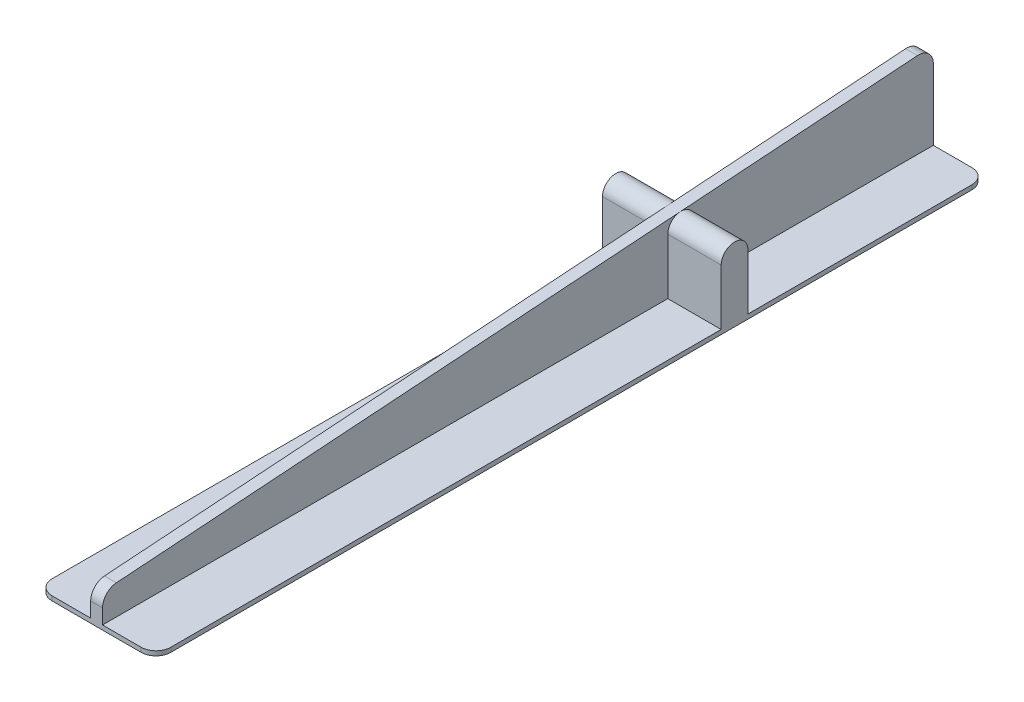
SolidWorks part; units mm, degrees
material "ABS"
ref_plane "Plan de face" through (0, 0, 0) normal (0, 0, 1) x (1, 0, 0)
ref_plane "Plan de dessus" through (0, 0, 0) normal (0, 1, 0) x (1, 0, 0)
ref_plane "Plan de droite" through (0, 0, 0) normal (1, 0, 0) x (0, 0, -1)
sketch "Esquisse1" plane through (0, 0, 0) normal (0, 0, 1) x (1, 0, 0)
  line L0 (2, 1.5) -> (20, 1.5)
  line L1 (-2, 41.5) -> (2, 41.5)
  line L2 (-2, 41.5) -> (-2, 1.5)
  line L4 (2, 41.5) -> (2, 1.5)
  line L5 (-20, 0) -> (20, 0)
  line L6 (-20, 0) -> (-20, 1.5)
  line L7 (-20, 1.5) -> (-2, 1.5)
  line L8 (20, 0) -> (20, 1.5)
  dimension "D1" = 1.5
  dimension "D2" = 40
  dimension "D3" = 4
  dimension "D4" = 40
  dimension "D5" = 18
extrude "Boss.-Extru.1" add sketch "Esquisse1" along normal blind 280 from offset 85 offset against normal yes
sketch "Esquisse3" plane through (2, 0, 0) normal (1, 0, 0) x (0, 0, -1)
  line L0 (85, 1.5) -> (85, 41.5) construction
  line L1 (-195, 41.5) -> (85, 41.5)
  line L2 (-195, 41.5) -> (-195, 11.1643)
  line L3 (-195, 11.1643) -> (85, 30.7438)
  line L4 (85, 41.5) -> (85, 30.7438)
  line L5 (0, 24.8) -> (0, 0) construction
  line L6 (-195, 1.5) -> (85, 1.5) construction
  dimension "D1" = 4
  dimension "D2" = 23.3
extrude "Enlèv. mat.-Extru.1" cut sketch "Esquisse3" against normal through all
sketch "Esquisse2" plane through (20, 0, 0) normal (1, 0, 0) x (0, 0, -1)
  line L1 (-4.5, 0) -> (4.5, 0)
  line L2 (-4.5, 0) -> (-4.5, 20.289)
  line L3 (-4.5, 20.289) -> (4.5, 20.289) construction
  line L4 (4.5, 0) -> (4.5, 20.289)
  line L5 (-195, 11.1643) -> (85, 30.7438) construction
  arc A0 (4.5, 20.289) -> (-4.5, 20.289) centre (0, 20.289) ccw
  dimension "D1" = 9
extrude "Boss.-Extru.2" add sketch "Esquisse2" against normal up to surface (40 mm away) up to face at (-20, 0.75, 55)
fillet "Congé1" radius 5 6 edges at (-20, 0.75, -85) (20, 0.75, -85) (0, 30.7438, -85) (-20, 0.75, 195) (20, 0.75, 195) (0, 11.1643, 195)
